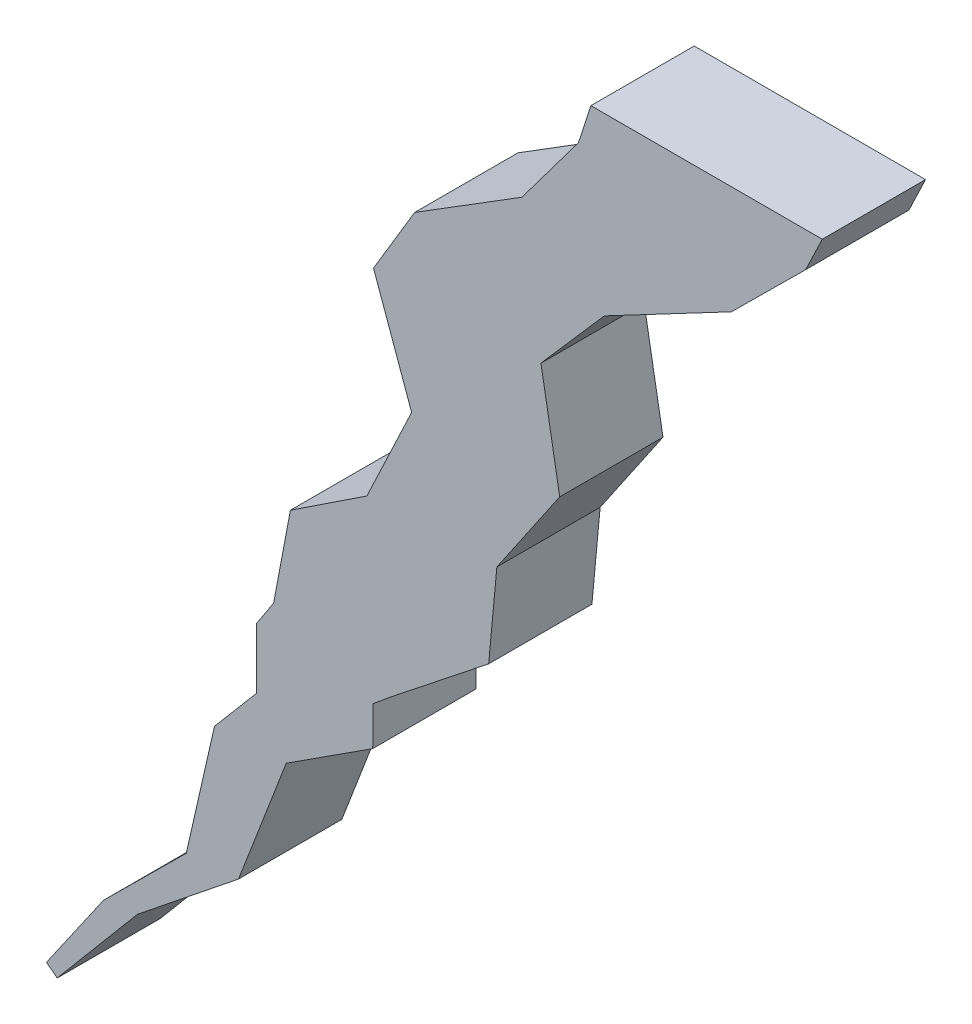
SolidWorks part; units mm, degrees
ref_plane "Ebene vorne" through (0, 0, 0) normal (0, 0, 1) x (1, 0, 0)
ref_plane "Ebene oben" through (0, 0, 0) normal (0, 1, 0) x (1, 0, 0)
ref_plane "Ebene rechts" through (0, 0, 0) normal (1, 0, 0) x (0, 0, -1)
sketch "Model" plane through (0, 0, 0) normal (0, 0, 1) x (1, 0, 0)
  line L30 (22.6696, 29.8312) -> (22.1883, 28.8233)
  line L31 (22.1883, 28.8233) -> (20.029, 26.6841)
  line L32 (20.029, 26.6841) -> (16.3393, 24.7372)
  line L33 (16.3393, 24.7372) -> (14.499, 22.6286)
  line L34 (14.499, 22.6286) -> (15.0444, 19.5374)
  line L35 (15.0444, 19.5374) -> (13.2183, 16.8612)
  line L36 (13.2183, 16.8612) -> (12.9803, 14.3043)
  line L37 (12.9803, 14.3043) -> (10.1291, 12.0445)
  line L38 (10.1291, 12.0445) -> (9.6268, 11.6274)
  line L39 (9.6268, 11.6274) -> (9.6128, 10.4885)
  line L40 (9.6128, 10.4885) -> (7.1006, 8.8647)
  line L41 (7.1006, 8.8647) -> (5.7152, 5.2588)
  line L42 (5.7152, 5.2588) -> (2.7755, 2.9011)
  line L43 (2.7755, 2.9011) -> (0.4498, 0.1373)
  line L44 (0.4498, 0.1373) -> (0.1367, 0.3757)
  line L45 (0.1367, 0.3757) -> (1.7937, 2.7647)
  line L46 (1.7937, 2.7647) -> (4.1966, 5.1472)
  line L47 (4.1966, 5.1472) -> (5.0166, 8.7524)
  line L48 (5.0166, 8.7524) -> (6.2415, 10.1973)
  line L49 (6.2415, 10.1973) -> (6.2333, 11.9417)
  line L50 (6.2333, 11.9417) -> (6.7347, 12.7106)
  line L51 (6.7347, 12.7106) -> (7.2214, 15.2895)
  line L52 (7.2214, 15.2895) -> (9.4429, 16.7582)
  line L53 (9.4429, 16.7582) -> (10.7426, 19.5095)
  line L54 (10.7426, 19.5095) -> (9.636, 22.5881)
  line L55 (9.636, 22.5881) -> (10.8314, 24.5854)
  line L56 (10.8314, 24.5854) -> (13.9488, 26.5277)
  line L57 (13.9488, 26.5277) -> (15.5877, 28.7178)
  line L58 (15.5877, 28.7178) -> (15.9498, 29.8312)
  line L59 (15.9498, 29.8312) -> (22.6696, 29.8312)
extrude "Aufsatz-Linear austragen1" add sketch "Model" along normal blind 3
